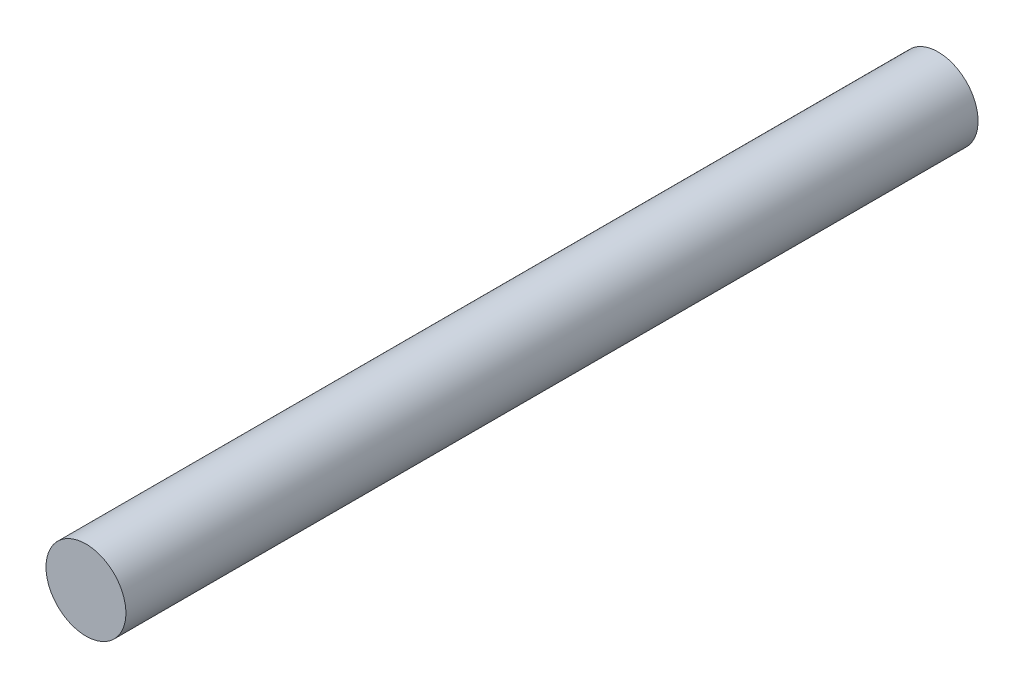
SolidWorks part; units mm, degrees
ref_plane "Front Plane" through (0, 0, 0) normal (0, 0, 1) x (1, 0, 0)
ref_plane "Top Plane" through (0, 0, 0) normal (0, 1, 0) x (1, 0, 0)
ref_plane "Right Plane" through (0, 0, 0) normal (1, 0, 0) x (0, 0, -1)
sketch "Sketch2" plane through (0, 0, 0) normal (0, 0, 1) x (1, 0, 0)
  circle A0 centre (0, 0) radius 14.2875
  dimension "D1" = 28.575
extrude "Boss-Extrude1" add sketch "Sketch2" along normal blind 304.8
